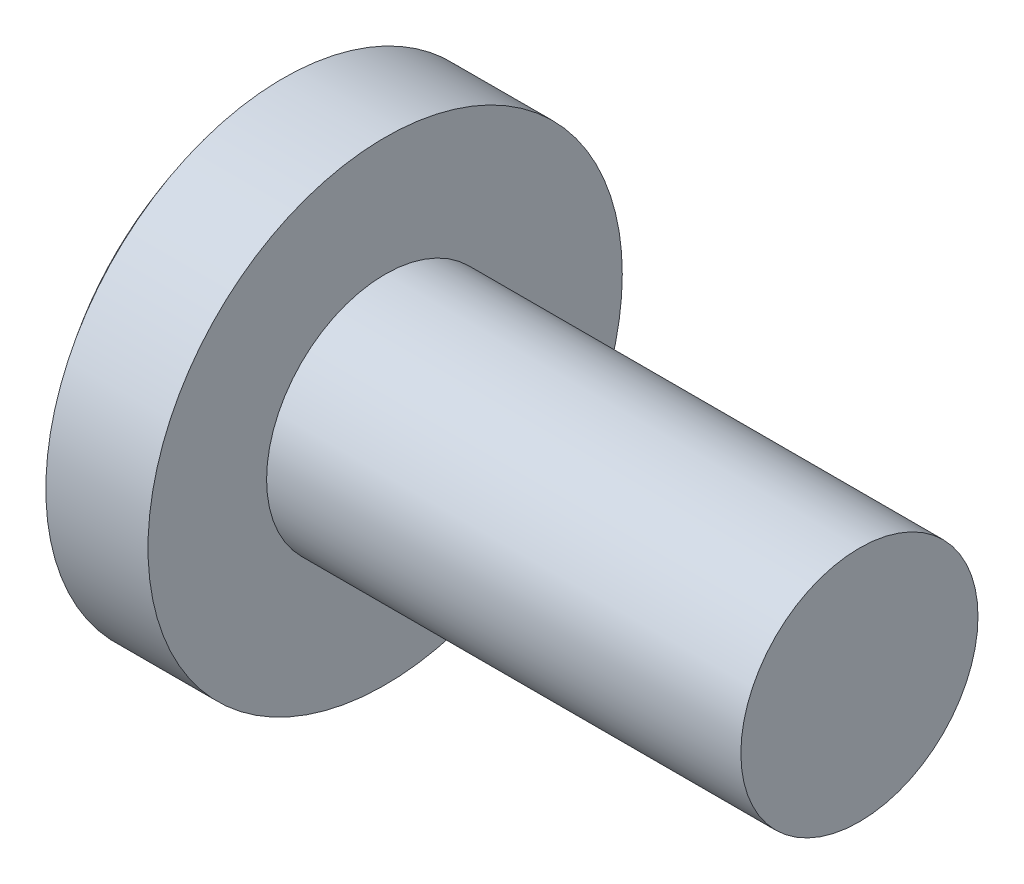
SolidWorks part; units mm, degrees
ref_plane "Front" through (0, 0, 0) normal (0, 0, 1) x (1, 0, 0)
ref_plane "Top" through (0, 0, 0) normal (0, 1, 0) x (1, 0, 0)
ref_plane "Right" through (0, 0, 0) normal (1, 0, 0) x (0, 0, -1)
sketch "Sketch1" plane through (0, 0, 0) normal (0, 0, 1) x (1, 0, 0)
  line L0 (11.1, 2) -> (4.5, 2)
  line L1 (3.1, 2.35) -> (3.1, 4)
  line L2 (3.1, 4) -> (1.3765, 4)
  line L3 (4.5, 2) -> (3.3865, 2.0503) construction
  line L4 (11.1, 2) -> (11.1, 0)
  line L5 (4.5158, 0) -> (-13.5157, 0) construction
  line L6 (11.1, 0) -> (0, 0)
  line L7 (4.5, 2) -> (3.1, 2)
  line L8 (3.1, 2) -> (3.1, 2.35)
  arc A0 (1.3765, 4) -> (0, 0) centre (6.5, 0) ccw
  arc A1 (3.1, 2.35) -> (3.3865, 2.0503) centre (3.4, 2.35) ccw construction
  dimension "r" = 0.3
  dimension "r1" = 6.5
  dimension "d" = 4
  dimension "dk" = 8
  dimension "l" = 8
  dimension "a" = 1.4
  dimension "da" = 4.7
  dimension "k" = 3.1
revolve "Base" add sketch "Sketch1" angle 360 about L5
cosmetic thread "ThreadCosmetic1" [suppressed] parameters "bb"=8, "THD_MINOR"=3.242
sketch "Sketch6" plane through (0, 0, 0) normal (1, 0, 0) x (0, 0, -1)
  line L0 (-1.9271, 0) -> (2.0512, 0) construction
  line L1 (0, 1.8651) -> (0, -2.0207) construction
  line L2 (0.44, 0.44) -> (0.44, 2.2)
  line L3 (0.44, 2.2) -> (-0.44, 2.2)
  line L4 (-0.44, 0.44) -> (-0.44, 2.2)
  line L5 (0.44, 0.44) -> (2.2, 0.44)
  line L6 (2.2, 0.44) -> (2.2, -0.44)
  line L7 (-2.2, 0.44) -> (-2.2, -0.44)
  line L8 (-0.44, 0.44) -> (-2.2, 0.44)
  line L9 (-0.44, -0.44) -> (-2.2, -0.44)
  line L10 (0.44, -0.44) -> (2.2, -0.44)
  line L11 (-0.44, -0.44) -> (-0.44, -2.2)
  line L12 (0.44, -2.2) -> (-0.44, -2.2)
  line L13 (0.44, -0.44) -> (0.44, -2.2)
  point P16 (-2.2, 0)
  point P17 (2.2, 0)
extrude "CrossRecess" cut sketch "Sketch6" along normal blind 2.17
fillet "Fillet5" radius 0.3 4 edges at (1.0999, -0.44, 0.44) (1.0999, -0.44, -0.44) (1.0999, 0.44, 0.44) (1.0999, 0.44, -0.44)
draft "Draft1" type of draft neutral plane draft angle 30 neutral plane "Right" faces to draft 4 face at (1.2808, -2.2, 0) face at (1.2808, 0, -2.2) face at (1.2808, 0, 2.2) face at (1.2808, 2.2, 0) neutral plane through (0, 0, 0) neutral plane normal (1, 0, 0) reverse direction yes parameters "D1"=30
sketch "Sketch7" plane through (0, 0, 0) normal (1, 0, 0) x (0, 0, -1)
  line L0 (-2.0126, 0) -> (1.9757, 0) construction
  line L1 (0, 1.9314) -> (0, -2.0126) construction
  line L2 (0, 0) -> (1.5555, 1.5555) construction
  line L3 (0, 0.6575) -> (1.5556, 1.5556)
  line L4 (-1.5402, 1.5402) -> (0, 0) construction
  line L5 (0.6575, 0) -> (1.5556, 1.5556)
  line L6 (0, -0.6575) -> (1.5556, -1.5556)
  line L7 (0.6575, 0) -> (1.5556, -1.5556)
  line L8 (-0.6575, 0) -> (-1.5556, -1.5556)
  line L9 (0, -0.6575) -> (-1.5556, -1.5556)
  line L10 (-0.6575, 0) -> (-1.5556, 1.5556)
  line L11 (0, 0.6575) -> (-1.5556, 1.5556)
  dimension "D3" = 15
  dimension "m" = 4.4
extrude "Cut-Extrude3" [suppressed] cut sketch "Sketch7" along normal blind 40.2 draft 9
sketch "Sketch8" plane through (0, 0, 0) normal (0, 0, 1) x (1, 0, 0)
  line L0 (-26.9, 2) -> (-28.65, 1.621)
  line L1 (-28.65, 1.621) -> (3.1, 1.621)
  line L2 (11.1, -2) -> (11.1, 2) construction
  line L3 (3.1, -4) -> (3.1, 4) construction
  line L6 (3.1, 1.621) -> (3.1, 4)
  line L7 (3.1, 4) -> (-26.9, 4)
  line L8 (-26.9, 4) -> (-26.9, 2)
  line L9 (73.4853, 0) -> (63.9694, 0) construction
  dimension "x" = 1.75
  dimension "d" = 4
  dimension "THD_MINOR" = 3.242
  dimension "b" = 38
sketch "Sketch9" plane through (0, 0, 0) normal (0, 0, 1) x (1, 0, 0)
  line L0 (11.1, 1.6718) -> (11.2895, 2)
  line L1 (11.2895, 2) -> (11.2895, 2.379)
  line L2 (11.2895, 2.379) -> (10.9105, 2.379)
  line L3 (10.9105, 2.379) -> (10.9105, 2)
  line L4 (10.9105, 2) -> (11.1, 1.6718)
  line L5 (11.1, -2) -> (11.1, 2) construction
  line L6 (0, 0) -> (76.7811, 0) construction
  dimension "D1" = 4
  dimension "D2" = 0.379
revolve "Cut-Revolve10" [suppressed] cut sketch "Sketch9" angle 360 about L6
pattern_linear "LPattern10" [suppressed] count 18 spacing 0.4548 along (1, 0, 0)
equation "\"D1@Sketch6\" = \"m@Sketch6\" / 5"
equation "\"D1@CrossRecess\" = 0.7*\"k@Sketch1\""
equation "\"D1@Sketch9\" = \"d@Sketch1\" "
equation "\"D2@Sketch9\" =  ( \"d@Sketch1\" - \"THD_MINOR@ThreadCosmetic1\" )  / 2"
equation "\"D3@LPattern10\" =\"D2@Sketch9\" * 1.2"
equation "\"D1@LPattern10\" = \"bb@ThreadCosmetic1\" / \"D3@LPattern10\" "
